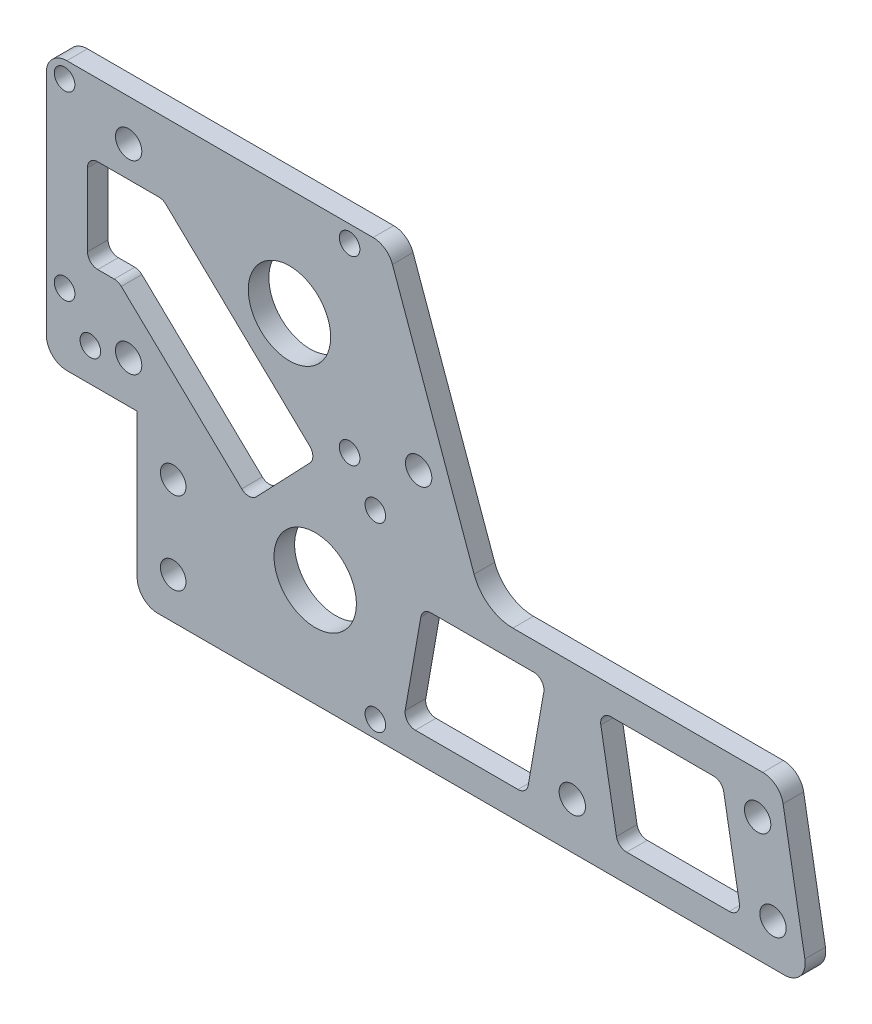
SolidWorks part; units mm, degrees
ref_plane "Front Plane" through (0, 0, 0) normal (0, 0, 1) x (1, 0, 0)
ref_plane "Top Plane" through (0, 0, 0) normal (0, 1, 0) x (1, 0, 0)
ref_plane "Right Plane" through (0, 0, 0) normal (1, 0, 0) x (0, 0, -1)
sketch "Sketch1" plane through (0, 0, 0) normal (0, 0, 1) x (1, 0, 0)
  line L4 (102.6928, 0) -> (-0.9114, 0)
  line L6 (98.2141, 25.4) -> (57.0135, 25.4)
  line L7 (51.0366, 29.6052) -> (38.4508, 64.6777)
  line L8 (35.4624, 66.7803) -> (-11.7499, 66.7803)
  line L9 (-14.9249, 63.6053) -> (-14.9249, 25.4)
  line L10 (-33.5059, 25.4) -> (9.947, 25.4) construction
  line L11 (-14.9249, 25.4) -> (-0.9114, 25.4)
  line L12 (-0.9114, 25.4) -> (-0.9114, 0)
  line L13 (98.2141, 25.4) -> (102.6928, 0)
  line L14 (46.7852, 41.4526) -> (38.4508, 64.6777) construction
  line L15 (13.7992, 0) -> (110.6303, 0) construction
  line L17 (-0.9114, 23.749) -> (-0.9114, 1.651) construction
  line L18 (-14.9249, 65.1928) -> (-14.9249, 36.2471) construction
  arc A2 (57.0135, 25.4) -> (51.0366, 29.6052) centre (57.0135, 31.75) cw
  arc A3 (38.4508, 64.6777) -> (35.4624, 66.7803) centre (35.4624, 63.6053) ccw
  arc A4 (-11.7499, 66.7803) -> (-14.9249, 63.6053) centre (-11.7499, 63.6053) ccw
  arc A7 (38.4508, 64.6777) -> (35.4624, 66.7803) centre (35.4624, 63.6053) ccw construction
  dimension "D2" = 80
  dimension "D4" = 3.175
  dimension "D1" = 25.4
  dimension "D3" = 25.4
  dimension "D5" = 7.9375
extrude "Boss-Extrude1" add sketch "Sketch1" along normal blind 3.175
sketch "Sketch2" plane through (0, 0, 3.175) normal (0, 0, 1) x (1, 0, 0)
  line L0 (26.5406, 16.5735) -> (13.8406, 16.5735) construction
  line L1 (22.5719, 50.2068) -> (9.8719, 50.2068) construction
  line L2 (35.8116, 2.6035) -> (-8.1304, 2.6035) construction
  line L3 (35.8116, 2.6035) -> (35.8116, 30.5435) construction
  line L4 (35.8116, 30.5435) -> (-8.1304, 30.5435) construction
  line L5 (-8.1304, 2.6035) -> (-8.1304, 30.5435) construction
  line L6 (35.8116, 2.6035) -> (-8.1304, 30.5435) construction
  line L7 (35.8116, 30.5435) -> (-8.1304, 2.6035) construction
  line L9 (31.8429, 36.2368) -> (-12.0991, 36.2368) construction
  line L10 (31.8429, 36.2368) -> (31.8429, 64.1768) construction
  line L11 (31.8429, 64.1768) -> (-12.0991, 64.1768) construction
  line L12 (-12.0991, 36.2368) -> (-12.0991, 64.1768) construction
  line L13 (31.8429, 36.2368) -> (-12.0991, 64.1768) construction
  line L14 (31.8429, 64.1768) -> (-12.0991, 36.2368) construction
  circle A0 centre (22.5719, 50.2068) radius 3.175 construction
  circle A1 centre (26.5406, 16.5735) radius 3.175 construction
  circle A2 centre (22.5719, 50.2068) radius 3.175 construction
  circle A3 centre (26.5406, 16.5735) radius 3.175 construction
  circle A4 centre (22.5719, 50.2068) radius 6.35
  circle A5 centre (26.5406, 16.5735) radius 6.35
  circle A6 centre (-8.1304, 30.5435) radius 1.5875
  circle A7 centre (35.8116, 30.5435) radius 1.5875
  circle A8 centre (35.8116, 2.6035) radius 1.5875
  circle A9 centre (-8.1304, 2.6035) radius 1.5875
  circle A10 centre (-12.0991, 36.2368) radius 1.5875
  circle A11 centre (31.8429, 36.2368) radius 1.5875
  circle A12 centre (31.8429, 64.1768) radius 1.5875
  circle A13 centre (-12.0991, 64.1768) radius 1.5875
  circle A14 centre (66.1803, 7.1437) radius 2.032 construction
  circle A15 centre (66.1803, 7.1437) radius 2.032
  dimension "D1" = 12.7
  dimension "D3" = 3.175
  dimension "D2" = 12.7
extrude "Cut-Extrude1" cut sketch "Sketch2" against normal through all
sketch "Sketch3" plane through (0, 0, 0) normal (0, 0, -1) x (-1, 0, 0)
  circle A0 centre (-42.4896, 39.1896) radius 2.032 construction
  circle A1 centre (-42.4896, 39.1896) radius 2.032
  circle A2 centre (-4.6449, 19.05) radius 1.9685 construction
  circle A3 centre (-4.6449, 6.35) radius 1.9685 construction
  circle A4 centre (-4.6449, 19.05) radius 1.9685
  circle A5 centre (-4.6449, 6.35) radius 1.9685
extrude "Cut-Extrude2" cut sketch "Sketch3" against normal through all
sketch "Sketch4" plane through (0, 0, 3.175) normal (0, 0, 1) x (1, 0, 0)
  line L0 (94.7553, 19.05) -> (97.1264, 6.35) construction
  line L1 (102.6928, 0) -> (98.2141, 25.4) construction
  line L2 (98.2141, 25.4) -> (57.0135, 25.4) construction
  circle A2 centre (66.1803, 7.1437) radius 2.032 construction
  circle A4 centre (94.7553, 19.05) radius 2.032
  circle A5 centre (97.1264, 6.35) radius 2.032
  circle A6 centre (-2.2249, 60.4303) radius 2.032 construction
  circle A7 centre (-2.2249, 60.4303) radius 2.032
  circle A8 centre (-2.2249, 31.8553) radius 2.032 construction
  circle A9 centre (-2.2249, 31.8553) radius 2.032
  dimension "D2" = 4.5089
  dimension "D1" = 12.7
  dimension "D3" = 4.3792
  dimension "D4" = 6.35
fillet "Fillet1" radius 3.175 4 edges at (102.6928, 0, 1.5875) (98.2141, 25.4, 1.5875) (-14.9249, 25.4, 1.5875) (-0.9114, 0, 1.5875)
extrude "Cut-Extrude3" cut sketch "Sketch4" against normal through all
sketch "Sketch5" plane through (0, 0, 0) normal (0, 0, -1) x (-1, 0, 0)
  line L0 (-3.065, 55.6678) -> (-26.8314, 32.966)
  line L1 (-26.8314, 32.966) -> (-16.3613, 22.005)
  line L2 (-16.3613, 22.005) -> (3.8124, 41.275)
  line L3 (3.8124, 41.275) -> (8.5749, 41.275)
  line L4 (8.5749, 41.275) -> (8.5749, 55.6678)
  line L5 (8.5749, 55.6678) -> (-3.065, 55.6678)
  line L6 (14.9249, 63.6053) -> (14.9249, 28.575) construction
  line L9 (-92.6555, 2.0723) -> (-89.2964, 21.1223)
  line L10 (-92.2707, 4.2545) -> (-89.2964, 21.1223)
  line L11 (-2.2636, 0) -> (-98.909, 0) construction
  line L12 (-89.2964, 21.1223) -> (-70.2464, 21.1223)
  line L13 (-92.2707, 4.2545) -> (-73.2207, 4.2545)
  line L14 (-73.2207, 4.2545) -> (-70.2464, 21.1223)
  line L15 (-66.1803, 0) -> (-66.1803, 25.4) construction
  line L16 (-95.55, 25.4) -> (-57.0135, 25.4) construction
  line L17 (-40.0899, 4.2545) -> (-59.1399, 4.2545)
  line L18 (-59.1399, 4.2545) -> (-62.1142, 21.1223)
  line L19 (-43.0642, 21.1223) -> (-62.1142, 21.1223)
  line L20 (-40.0899, 4.2545) -> (-43.0642, 21.1223)
  line L21 (11.7499, 25.4) -> (0.9114, 25.4) construction
  circle A1 centre (2.2249, 60.4303) radius 2.032 construction
  circle A2 centre (-22.5719, 50.2068) radius 6.35 construction
  circle A3 centre (-26.5406, 16.5735) radius 6.35 construction
  circle A4 centre (2.2249, 31.8553) radius 2.032 construction
  point P16 (-66.1803, 7.1437)
  dimension "D3" = 4.2545
  dimension "D4" = 19.05
  dimension "D1" = 6.35
  dimension "D5" = 4.7625
  dimension "D6" = 9.525
  dimension "D7" = 11.1125
  dimension "D8" = 5.715
  dimension "D9" = 15.875
  dimension "D10" = 1.5875
  dimension "D2" = 9.525
extrude "Cut-Extrude4" cut sketch "Sketch5" against normal up to next
fillet "Fillet2" radius 1.5875 14 edges at (73.2207, 4.2545, 1.5875) (92.2707, 4.2545, 1.5875) (89.2964, 21.1223, 1.5875) (70.2464, 21.1223, 1.5875) (40.0899, 4.2545, 1.5875) (59.1399, 4.2545, 1.5875) (62.1142, 21.1223, 1.5875) (43.0642, 21.1223, 1.5875) (16.3613, 22.005, 1.5875) (26.8314, 32.966, 1.5875) (3.065, 55.6678, 1.5875) (-8.5749, 41.275, 1.5875) (-8.5749, 55.6678, 1.5875) (-3.8124, 41.275, 1.5875)
